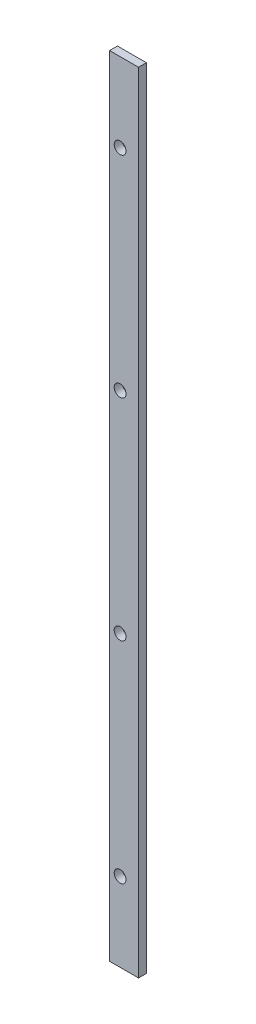
SolidWorks part; units mm, degrees
ref_plane "Plan de face" through (0, 0, 0) normal (0, 0, 1) x (1, 0, 0)
ref_plane "Plan de dessus" through (0, 0, 0) normal (0, 1, 0) x (1, 0, 0)
ref_plane "Plan de droite" through (0, 0, 0) normal (1, 0, 0) x (0, 0, -1)
sketch "Esquisse1" plane through (0, 0, 0) normal (0, 0, 1) x (1, 0, 0)
  line L1 (0, 0) -> (8, 0)
  line L2 (0, 0) -> (0, 300)
  line L3 (0, 300) -> (8, 300)
  line L4 (8, 0) -> (8, 300)
  dimension "D1" = 300
  dimension "D2" = 8
extrude "Boss.-Extru.1" add sketch "Esquisse1" along normal blind 3
sketch "Esquisse2" plane through (0, 0, 3) normal (0, 0, 1) x (1, 0, 0)
  line L0 (4, 0) -> (4, 300) construction
  line L1 (0, 0) -> (8, 0) construction
  line L2 (8, 300) -> (0, 300) construction
  line L3 (4, 150) -> (0, 150) construction
  line L4 (0, 300) -> (0, 0) construction
  circle A0 centre (4, 110) radius 2.25
  circle A1 centre (4, 30) radius 2.25
  circle A2 centre (4, 270) radius 2.25
  circle A3 centre (4, 190) radius 2.25
  dimension "D1" = 4.5
  dimension "D3" = 80
  dimension "D2" = 80
extrude "Enlèv. mat.-Extru.1" cut sketch "Esquisse2" against normal through all
ref_plane "Plan1" through (0, 0, 3) normal (0, -1, 0) x (-1, 0, 0)
sketch "Esquisse4" plane through (0, 0, 3) normal (0, 0, 1) x (1, 0, 0)
  line L0 (8, 300) -> (0, 300) construction
  line L1 (8, 0) -> (11, 0)
  line L2 (8, 0) -> (8, 300)
  line L3 (8, 300) -> (11, 300)
  line L4 (11, 0) -> (11, 300)
  dimension "D1" = 3
extrude "Boss.-Extru.2" add sketch "Esquisse4" against normal up to vertex (3 mm away)
